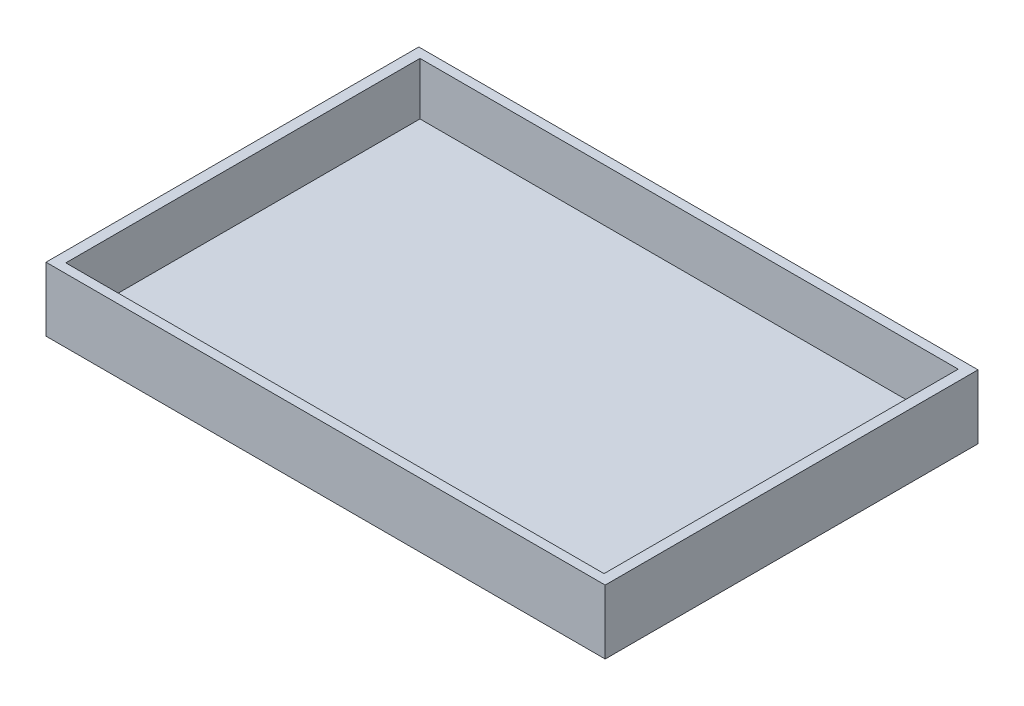
SolidWorks part; units mm, degrees
ref_plane "Plan de face" through (0, 0, 0) normal (0, 0, 1) x (1, 0, 0)
ref_plane "Plan de dessus" through (0, 0, 0) normal (0, 1, 0) x (1, 0, 0)
ref_plane "Plan de droite" through (0, 0, 0) normal (1, 0, 0) x (0, 0, -1)
sketch "Esquisse1" plane through (0, 0, 0) normal (0, 1, 0) x (1, 0, 0)
  line L1 (-24, -16) -> (24, -16)
  line L2 (-24, -16) -> (-24, 16)
  line L3 (-24, 16) -> (24, 16)
  line L4 (24, -16) -> (24, 16)
  line L5 (-24, -16) -> (24, 16) construction
  line L6 (-24, 16) -> (24, -16) construction
  point P0 (0, 0)
  dimension "D1" = 48
  dimension "D2" = 32
extrude "Boss.-Extru.1" add sketch "Esquisse1" along normal blind 5.5 contours L3 L4 L1 L2
sketch "Esquisse2" plane through (0, 5.5, 0) normal (0, 1, 0) x (1, 0, 0)
  line L1 (-23.1, -15.2) -> (23.1, -15.2)
  line L2 (-23.1, -15.2) -> (-23.1, 15.2)
  line L3 (-23.1, 15.2) -> (23.1, 15.2)
  line L4 (23.1, -15.2) -> (23.1, 15.2)
  line L5 (-23.1, -15.2) -> (23.1, 15.2) construction
  line L6 (-23.1, 15.2) -> (23.1, -15.2) construction
  point P0 (0, 0)
  dimension "D1" = 46.2
  dimension "D2" = 30.4
extrude "Enlèv. mat.-Extru.1" cut sketch "Esquisse2" against normal blind 4.5
